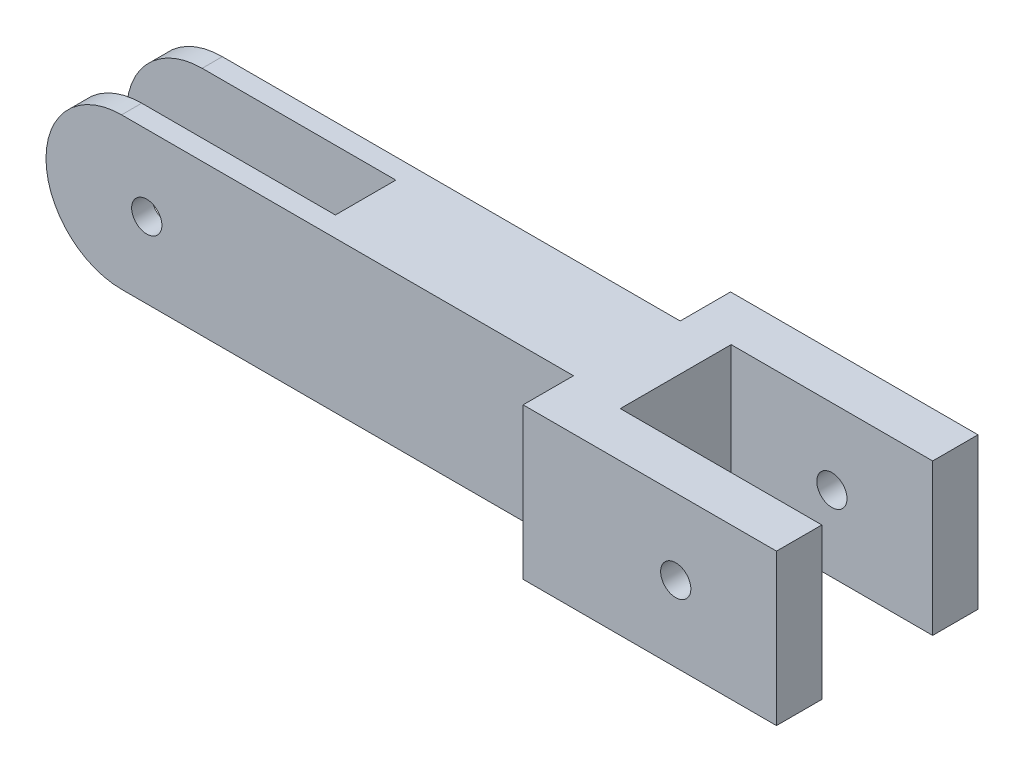
SolidWorks part; units mm, degrees
material "6063-O"
ref_plane "Ön Düzlem" through (0, 0, 0) normal (0, 0, 1) x (1, 0, 0)
ref_plane "Üst Düzlem" through (0, 0, 0) normal (0, 1, 0) x (1, 0, 0)
ref_plane "Sağ Düzlem" through (0, 0, 0) normal (1, 0, 0) x (0, 0, -1)
sketch "Çizim1" plane through (0, 0, 0) normal (0, 0, 1) x (1, 0, 0)
  line L1 (-12.5, 7.5) -> (57.5, 7.5)
  line L3 (-12.5, -7.5) -> (57.5, -7.5)
  line L4 (57.5, 7.5) -> (57.5, -7.5)
  arc A0 (-12.5, 7.5) -> (-12.5, -7.5) centre (-12.5, 0) ccw
  point P0 (0, 0)
  dimension "D1" = 15
  dimension "D4" = 15
  dimension "D2" = 70
extrude "Yükseklik-Ekstrüzyon1" add sketch "Çizim1" along normal mid plane 20
sketch "Çizim2" plane through (0, 0, 0) normal (0, 0, 1) x (1, 0, 0)
  line L0 (-12.5, -7.5) -> (57.5, -7.5) construction
  line L1 (6.7199, -7.5) -> (-13.2801, -7.5)
  line L2 (6.7199, -7.5) -> (6.7199, 7.5)
  line L3 (6.7199, 7.5) -> (-13.2801, 7.5)
  arc A0 (-13.2801, 7.5) -> (-13.2801, -7.5) centre (-13.2801, 0) ccw
  point P0 (-10, 0)
  dimension "D3" = 15
  dimension "D1" = 20
extrude "Kes-Ekstrüzyon1" cut sketch "Çizim2" against normal mid plane 6
sketch "Çizim4" plane through (0, 0, 0) normal (0, 0, 1) x (1, 0, 0)
  circle A0 centre (-10, 0) radius 1.5
  arc A1 (-12.5, 7.5) -> (-12.5, -7.5) centre (-12.5, 0) ccw construction
  point P7 (-20, 0)
  dimension "D2" = 3
  dimension "D1" = 10
extrude "Kes-Ekstrüzyon2" cut sketch "Çizim4" against normal mid plane 15
sketch "Çizim5" plane through (0, 0, 0) normal (0, 0, 1) x (1, 0, 0)
  line L1 (37.5, -9.3201) -> (57.5, -9.3201)
  line L2 (37.5, -9.3201) -> (37.5, 7.5)
  line L3 (37.5, 7.5) -> (57.5, 7.5)
  line L4 (57.5, -9.3201) -> (57.5, 7.5)
  line L5 (37.5, -9.3201) -> (57.5, 7.5) construction
  line L6 (37.5, 7.5) -> (57.5, -9.3201) construction
  point P0 (47.5, -0.9101)
  dimension "D1" = 20
extrude "Kes-Ekstrüzyon4" cut sketch "Çizim5" against normal mid plane 11
sketch "Çizim6" plane through (0, 0, 10) normal (0, 0, 1) x (1, 0, 0)
  line L0 (57.5, 7.5) -> (57.5, -7.5) construction
  circle A0 centre (47.5, 0) radius 1.5
  dimension "D1" = 3
  dimension "D2" = 10
extrude "Kes-Ekstrüzyon5" cut sketch "Çizim6" against normal blind 19
sketch "Çizim7" plane through (0, 0, 0) normal (0, 1, 0) x (1, 0, 0)
  line L0 (32.3533, -10) -> (32.3533, -5)
  line L1 (-12.5, -10) -> (57.5, -10) construction
  line L2 (32.3533, -5) -> (-23.4033, -5)
  line L3 (-23.4033, -5) -> (-23.4033, 5)
  line L4 (-23.4033, 5) -> (32.9411, 5)
  line L5 (32.9411, 5) -> (32.9411, 10)
  line L6 (-12.5, 10) -> (57.5, 10) construction
  line L7 (32.9411, 10) -> (-29.1973, 10)
  line L8 (-29.1973, 10) -> (-29.1973, -10)
  line L9 (-29.1973, -10) -> (32.3533, -10)
  dimension "D1" = 5
  dimension "D2" = 5
extrude "Kes-Ekstrüzyon6" cut sketch "Çizim7" against normal mid plane 24
